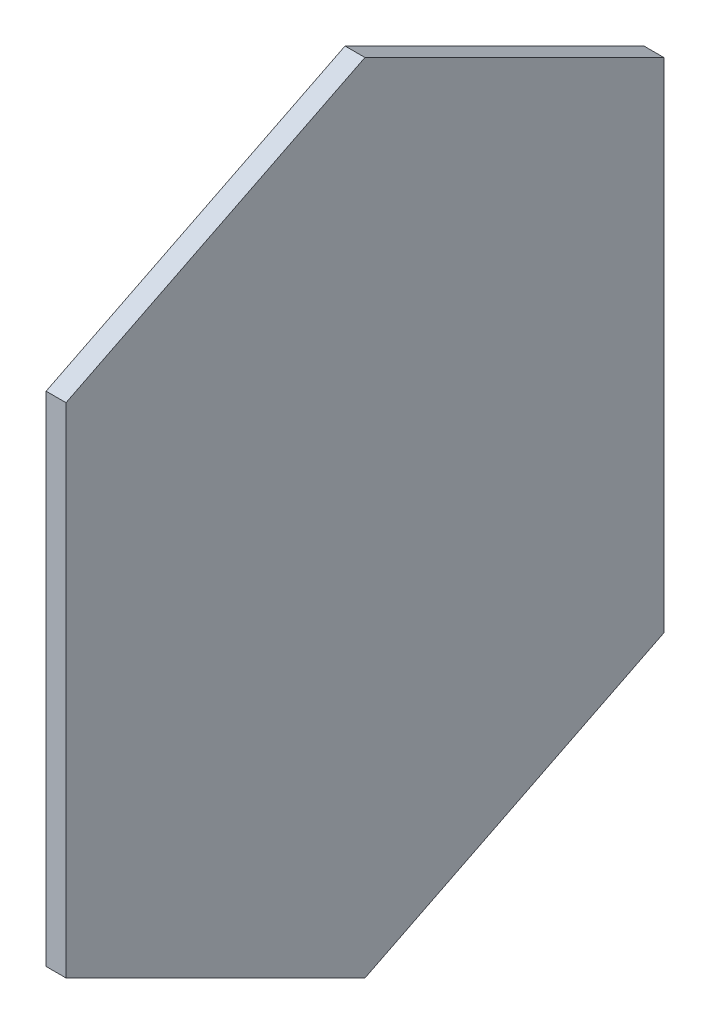
SolidWorks part; units mm, degrees
ref_plane "Front Plane" through (0, 0, 0) normal (0, 0, 1) x (1, 0, 0)
ref_plane "Top Plane" through (0, 0, 0) normal (0, 1, 0) x (1, 0, 0)
ref_plane "Right Plane" through (0, 0, 0) normal (1, 0, 0) x (0, 0, -1)
sketch "Sketch1" plane through (0, 0, 0) normal (1, 0, 0) x (0, 0, -1)
  line L0 (-381, 317.5) -> (-381, -317.5)
  line L1 (381, 317.5) -> (381, -317.5)
  line L2 (-381, -317.5) -> (0, -508)
  line L3 (0, -508) -> (381, -317.5)
  line L4 (381, 317.5) -> (0, 508)
  line L5 (0, 508) -> (-381, 317.5)
  point P4 (-381, 0)
  point P5 (0, -508)
  point P7 (0, 508)
  point P8 (381, 0)
  point P11 (0, 0)
  point P12 (0, 0)
  point P13 (381, 0)
  point P14 (0, 0)
  dimension "D1" = 635
  dimension "D2" = 762
  dimension "D3" = 381
  dimension "D4" = 508
  dimension "D5" = 508
extrude "Boss-Extrude1" add sketch "Sketch1" along normal blind 25.4 contours L5 L0 L2 L3 L1 L4
